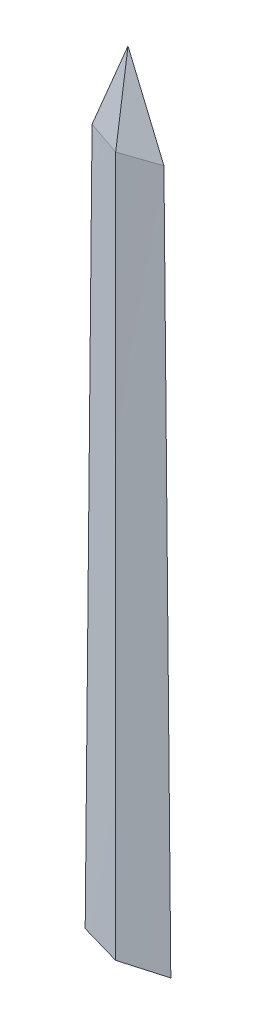
SolidWorks part; units mm, degrees
ref_plane "Front Plane" through (0, 0, 0) normal (0, 0, 1) x (1, 0, 0)
ref_plane "Top Plane" through (0, 0, 0) normal (0, 1, 0) x (1, 0, 0)
ref_plane "Right Plane" through (0, 0, 0) normal (1, 0, 0) x (0, 0, -1)
sketch "Sketch1" plane through (0, 0, 0) normal (0, 0, 1) x (1, 0, 0)
  line L0 (142.4212, 465.168) -> (219.716, 465.168)
  line L1 (219.716, 465.168) -> (213.5025, 1096.9676)
  line L2 (213.5025, 1096.9676) -> (181.0686, 1174.3372)
  line L3 (181.0686, 1174.3372) -> (148.6348, 1096.9676)
  line L4 (148.6348, 1096.9676) -> (142.4212, 465.168)
  point P2 (181.0686, 465.168)
extrude "Boss-Extrude1" add sketch "Sketch1" along normal blind 11.1125 and the other way blind 11.1125
sketch "Sketch2" plane through (0, 465.168, 0) normal (0, -1, 0) x (1, 0, 0)
  line L0 (142.4212, 0) -> (181.0686, 11.1125)
  line L1 (142.4212, -11.1125) -> (142.4212, 11.1125) construction
  line L2 (142.4212, 11.1125) -> (219.716, 11.1125) construction
  line L3 (181.0686, 11.1125) -> (219.716, 0)
  line L4 (219.716, -11.1125) -> (219.716, 11.1125) construction
  line L8 (142.4212, 0) -> (137.8486, 0)
  line L9 (137.8486, 0) -> (137.8486, 15.2584)
  line L10 (137.8486, 15.2584) -> (222.7051, 15.2584)
  line L11 (222.7051, 15.2584) -> (222.7051, 0)
  line L12 (222.7051, 0) -> (219.716, 0)
ref_plane "Plane1" through (0, 1096.9676, 0) normal (0, 1, 0) x (1, 0, 0)
sketch "Sketch3" plane through (0, 1096.9676, 0) normal (0, 1, 0) x (1, 0, 0)
  line L1 (148.6348, 11.1125) -> (148.6348, -11.1125) construction
  line L3 (213.5025, 11.1125) -> (213.5025, -11.1125) construction
  line L4 (213.5025, 0) -> (181.0686, -11.1125)
  line L5 (181.0686, -11.1125) -> (148.6348, 0)
  line L6 (148.6348, 0) -> (137.8486, 0)
  line L7 (137.8486, 0) -> (137.8486, -15.2584)
  line L8 (137.8486, -15.2584) -> (222.7051, -15.2584)
  line L9 (222.7051, -15.2584) -> (222.7051, 0)
  line L10 (222.7051, 0) -> (213.5025, 0)
loft "Cut-Loft1" cut profiles "Sketch2", "Sketch3"
mirror "Mirror1" about plane through (0, 0, 0) normal (0, 0, 1) of "Cut-Loft1"
ref_plane "Plane2" through (-32.1031, 13.4578, 93.6987) normal (-0.3212, 0.1346, 0.9374) x (0.947, 0.0457, 0.3179)
sketch "Sketch5" plane through (-32.1031, 13.4578, 93.6987) normal (-0.3212, 0.1346, 0.9374) x (0.947, 0.0457, 0.3179)
  line L1 (164.4105, 1280.8293) -> (274.288, 1280.8293)
  line L2 (164.4105, 1280.8293) -> (164.4105, 997.7782)
  line L3 (164.4105, 997.7782) -> (274.288, 997.7782)
  line L4 (274.288, 1280.8293) -> (274.288, 997.7782)
extrude "Cut-Extrude2" cut sketch "Sketch5" along normal through all
ref_plane "Plane3" through (69.4583, 29.1174, 202.7265) normal (0.3212, 0.1346, 0.9374) x (0.947, -0.0457, -0.3179)
sketch "Sketch6" plane through (69.4583, 29.1174, 202.7265) normal (0.3212, 0.1346, 0.9374) x (0.947, -0.0457, -0.3179)
  line L1 (57.1921, 1173.3831) -> (206.3136, 1173.3831)
  line L2 (57.1921, 1173.3831) -> (57.1921, 1064.4614)
  line L3 (57.1921, 1064.4614) -> (206.3136, 1064.4614)
  line L4 (206.3136, 1173.3831) -> (206.3136, 1064.4614)
extrude "Cut-Extrude3" cut sketch "Sketch6" along normal through all
mirror "Mirror2" about plane through (0, 0, 0) normal (0, 0, 1) of "Cut-Extrude2", "Cut-Extrude3"
sketch "Sketch7" plane through (0, 465.168, 0) normal (0, -1, 0) x (1, 0, 0)
  circle A0 centre (181.0686, 0) radius 4.7625
  dimension "D1" = 9.525
extrude "Cut-Extrude4" cut sketch "Sketch7" against normal blind 635
